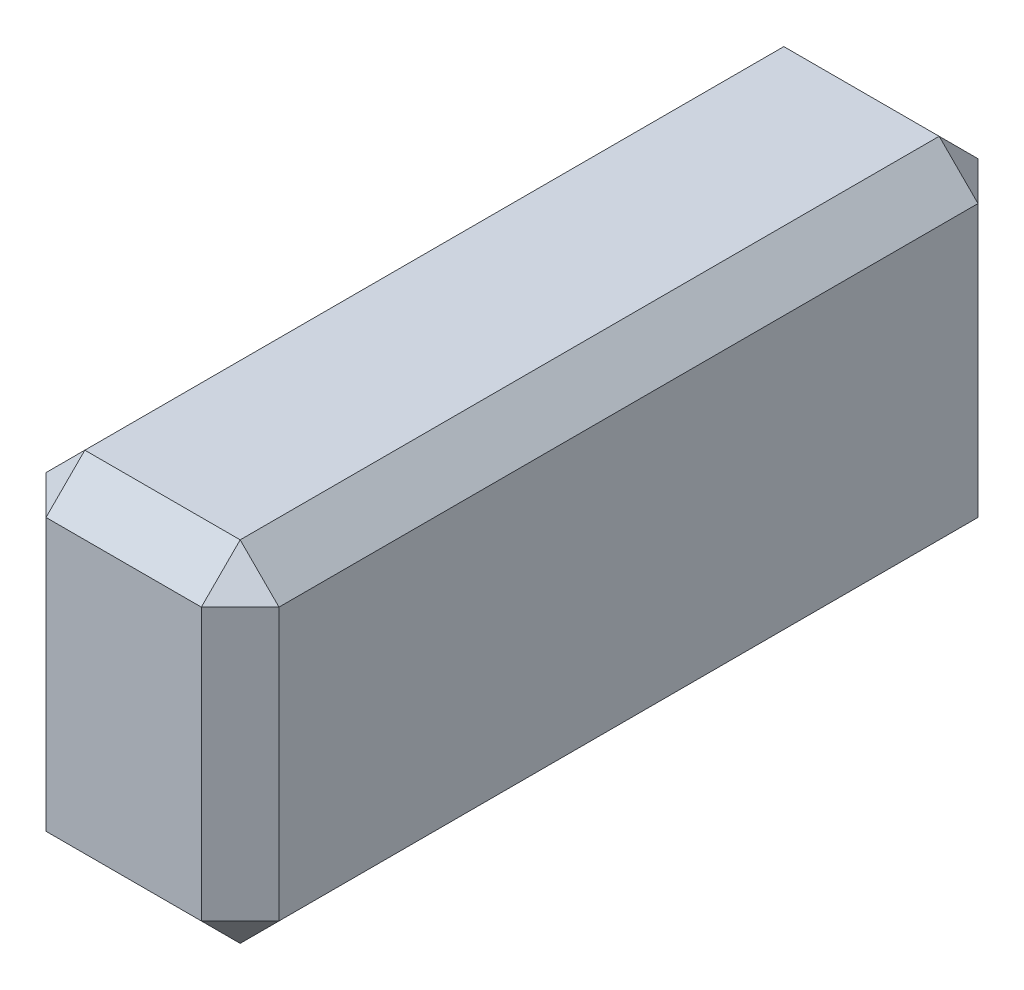
SolidWorks part; units mm, degrees
ref_plane "Front Plane" through (0, 0, 0) normal (0, 0, 1) x (1, 0, 0)
ref_plane "Top Plane" through (0, 0, 0) normal (0, 1, 0) x (1, 0, 0)
ref_plane "Right Plane" through (0, 0, 0) normal (1, 0, 0) x (0, 0, -1)
sketch "Sketch1" plane through (0, 0, 0) normal (0, 0, 1) x (1, 0, 0)
  line L1 (-1.5, -2.25) -> (1.5, -2.25)
  line L2 (-1.5, -2.25) -> (-1.5, 2.25)
  line L3 (-1.5, 2.25) -> (1.5, 2.25)
  line L4 (1.5, -2.25) -> (1.5, 2.25)
  line L5 (-1.5, -2.25) -> (1.5, 2.25) construction
  line L6 (-1.5, 2.25) -> (1.5, -2.25) construction
  point P0 (0, 0)
  dimension "D1" = 4.5
  dimension "D2" = 3
extrude "Boss-Extrude1" add sketch "Sketch1" along normal blind 10
chamfer "Chamfer1" distance 0.5 angle 45 12 edges at (0, -2.25, 10) (0, -2.25, 0) (0, 2.25, 10) (-1.5, 2.25, 5) (-1.5, 0, 10) (-1.5, -2.25, 5) (-1.5, 0, 0) (0, 2.25, 0) (1.5, -2.25, 5) (1.5, 0, 10) (1.5, 2.25, 5) (1.5, 0, 0)
